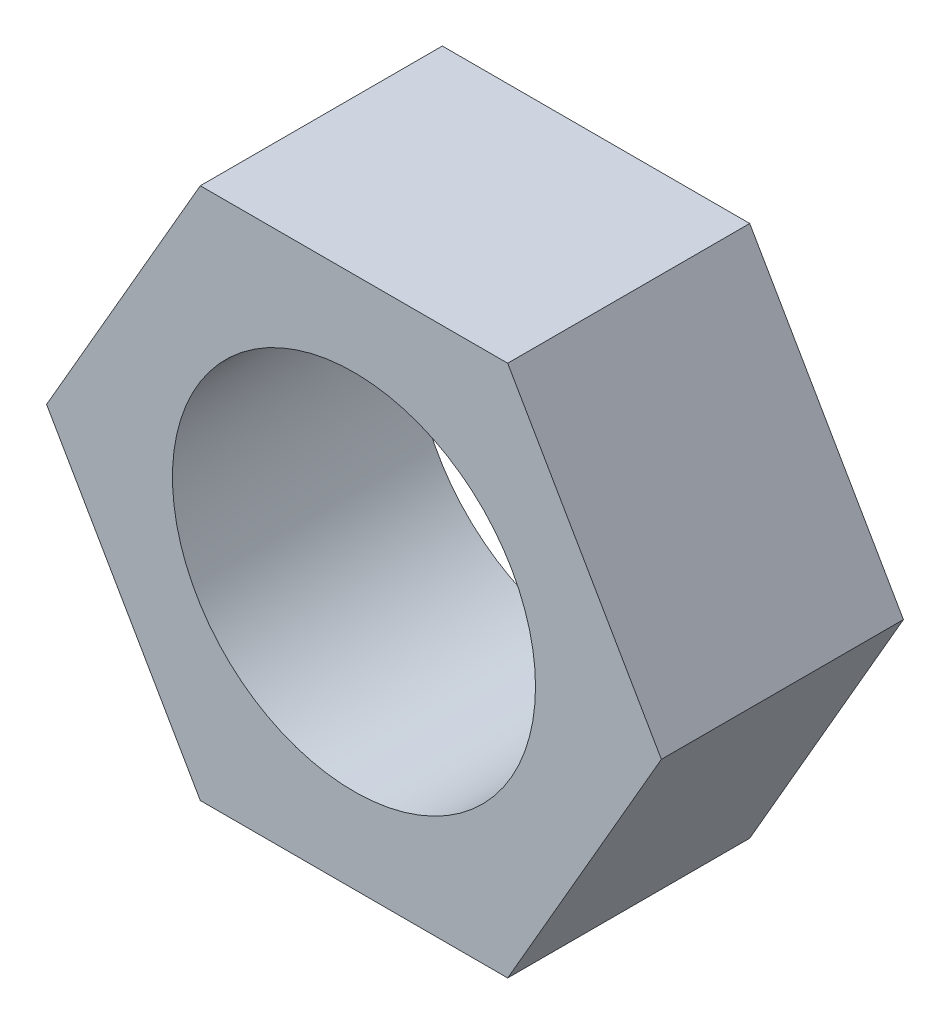
SolidWorks part; units mm, degrees
ref_plane "Front Plane" through (0, 0, 0) normal (0, 0, 1) x (1, 0, 0)
ref_plane "Top Plane" through (0, 0, 0) normal (0, 1, 0) x (1, 0, 0)
ref_plane "Right Plane" through (0, 0, 0) normal (1, 0, 0) x (0, 0, -1)
sketch "Sketch1" plane through (0, 0, 0) normal (0, 0, 1) x (1, 0, 0)
  line L1 (1.27, 2.1997) -> (-1.27, 2.1997)
  line L2 (-1.27, 2.1997) -> (-2.54, 0)
  line L3 (-2.54, 0) -> (-1.27, -2.1997)
  line L4 (-1.27, -2.1997) -> (1.27, -2.1997)
  line L5 (1.27, -2.1997) -> (2.54, 0)
  line L6 (2.54, 0) -> (1.27, 2.1997)
  circle A0 centre (0, 0) radius 2.1997 construction
  circle A1 centre (0, 0) radius 1.5
  dimension "D2" = 3
  dimension "D1" = 5.08
extrude "Boss-Extrude1" add sketch "Sketch1" along normal blind 2
